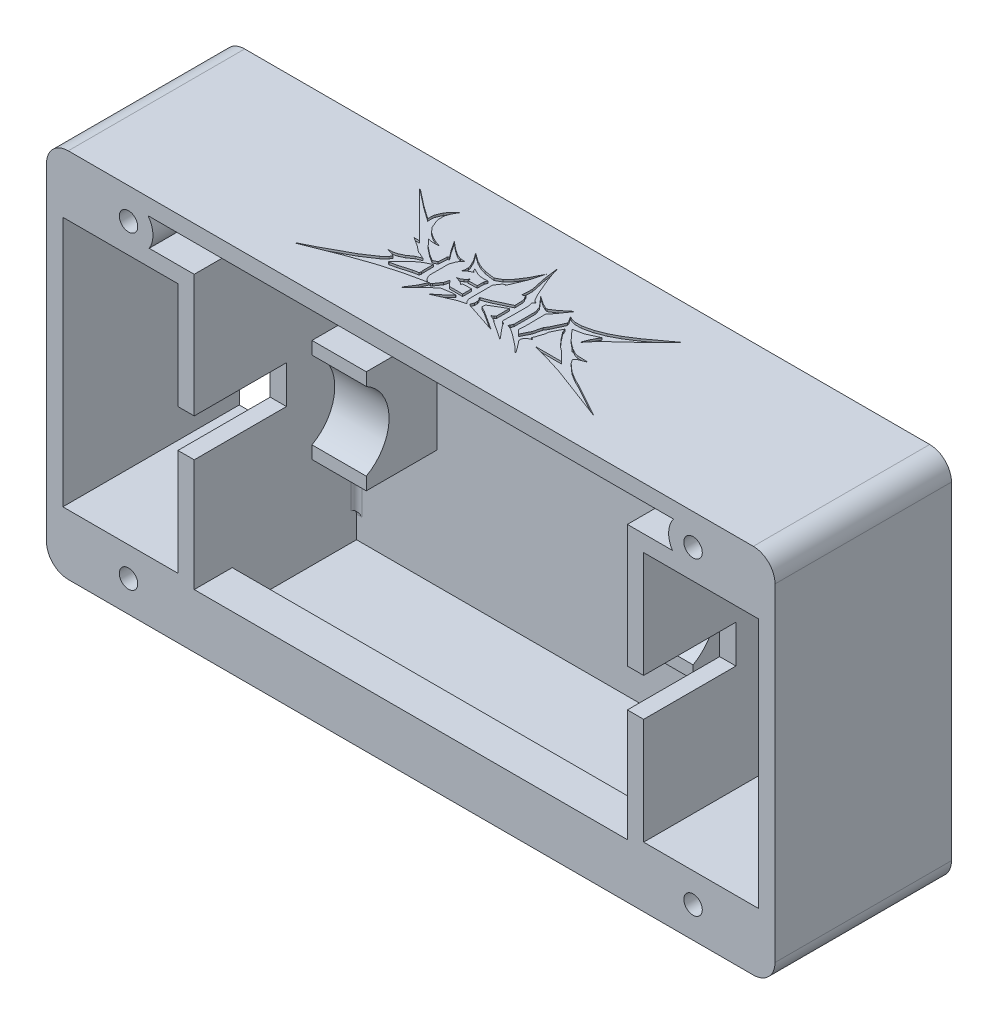
SolidWorks part; units mm, degrees
material "Overture Super PLA Plus"
ref_plane "Front Plane" through (0, 0, 0) normal (0, 0, 1) x (1, 0, 0)
ref_plane "Top Plane" through (0, 0, 0) normal (0, 1, 0) x (1, 0, 0)
ref_plane "Right Plane" through (0, 0, 0) normal (1, 0, 0) x (0, 0, -1)
sketch "Base_Footprint" plane through (0, 0, 0) normal (0, 0, 1) x (1, 0, 0)
  line L1 (-67.1, -34.2) -> (67.1, -34.2)
  line L2 (-67.1, -34.2) -> (-67.1, 34.2)
  line L3 (-67.1, 34.2) -> (67.1, 34.2)
  line L4 (67.1, -34.2) -> (67.1, 34.2)
  dimension "R1_Width" = 134.2
  dimension "R1_Length" = 68.4
  dimension "R1_X" = 67.1
  dimension "R1_Y" = 34.2
extrude "Unbroken_Floor" add sketch "Base_Footprint" along normal blind 2.6
sketch "Shell_Profile" plane through (0, 0, 0) normal (0, 0, 1) x (1, 0, 0)
  line L1 (-67.1, -34.2) -> (67.1, -34.2)
  line L2 (-67.1, -34.2) -> (-67.1, 34.2)
  line L3 (-67.1, 34.2) -> (67.1, 34.2)
  line L4 (67.1, -34.2) -> (67.1, 34.2)
  line L6 (-64.1, -31.2) -> (64.1, -31.2)
  line L7 (-64.1, -31.2) -> (-64.1, 31.2)
  line L8 (-64.1, 31.2) -> (64.1, 31.2)
  line L9 (64.1, -31.2) -> (64.1, 31.2)
  dimension "R1_Width" = 134.2
  dimension "R1_Length" = 68.4
  dimension "R1_X" = 67.1
  dimension "R1_Y" = 34.2
  dimension "R2_Width" = 128.2
  dimension "R2_Length" = 62.4
  dimension "R2_X" = 64.1
  dimension "R2_Y" = 31.2
extrude "Three_mm_Perimeter" add sketch "Shell_Profile" along normal blind 32.5
sketch "Wheel_Well_Profile" plane through (0, 0, 0) normal (0, 0, 1) x (1, 0, 0)
  line L1 (42.9, -23.1) -> (64.1, -23.1)
  line L2 (42.9, -23.1) -> (42.9, 23.1)
  line L3 (42.9, 23.1) -> (64.1, 23.1)
  line L4 (64.1, -23.1) -> (64.1, 23.1)
  line L6 (-64.1, -23.1) -> (-42.9, -23.1)
  line L7 (-64.1, -23.1) -> (-64.1, 23.1)
  line L8 (-64.1, 23.1) -> (-42.9, 23.1)
  line L9 (-42.9, -23.1) -> (-42.9, 23.1)
  dimension "R2_X" = 64.1
  dimension "R1_Width" = 21.2
  dimension "R1_Length" = 46.2
  dimension "R1_X" = 42.9
  dimension "R1_Y" = 23.1
  dimension "R2_Width" = 21.2
  dimension "R2_Length" = 46.2
  dimension "R2_Y" = 23.1
extrude "Open_Wheel_Wells" cut sketch "Wheel_Well_Profile" against normal blind 38 from offset 36
sketch "Wheel_Guard_Profile" plane through (0, 0, 0) normal (0, 0, 1) x (1, 0, 0)
  line L1 (39.9, -23.1) -> (42.9, -23.1)
  line L2 (39.9, -23.1) -> (39.9, 23.1)
  line L3 (39.9, 23.1) -> (42.9, 23.1)
  line L4 (42.9, -23.1) -> (42.9, 23.1)
  line L6 (-42.9, -23.1) -> (-39.9, -23.1)
  line L7 (-42.9, -23.1) -> (-42.9, 23.1)
  line L8 (-42.9, 23.1) -> (-39.9, 23.1)
  line L9 (-39.9, -23.1) -> (-39.9, 23.1)
  dimension "R1_Width" = 3
  dimension "R1_Length" = 46.2
  dimension "R1_X" = 39.9
  dimension "R1_Y" = 23.1
  dimension "R2_Width" = 3
  dimension "R2_Length" = 46.2
  dimension "R2_X" = 42.9
  dimension "R2_Y" = 23.1
extrude "Inner_Wheel_Guards" add sketch "Wheel_Guard_Profile" along normal blind 32.5
sketch "Wheel_Return_Profile" plane through (0, 0, 0) normal (0, 0, 1) x (1, 0, 0)
  line L1 (-64.1, -26.1) -> (-39.9, -26.1)
  line L2 (-64.1, -26.1) -> (-64.1, -23.1)
  line L3 (-64.1, -23.1) -> (-39.9, -23.1)
  line L4 (-39.9, -26.1) -> (-39.9, -23.1)
  line L6 (-64.1, 23.1) -> (-39.9, 23.1)
  line L7 (-64.1, 23.1) -> (-64.1, 26.1)
  line L8 (-64.1, 26.1) -> (-39.9, 26.1)
  line L9 (-39.9, 23.1) -> (-39.9, 26.1)
  line L11 (39.9, -26.1) -> (64.1, -26.1)
  line L12 (39.9, -26.1) -> (39.9, -23.1)
  line L13 (39.9, -23.1) -> (64.1, -23.1)
  line L14 (64.1, -26.1) -> (64.1, -23.1)
  line L16 (39.9, 23.1) -> (64.1, 23.1)
  line L17 (39.9, 23.1) -> (39.9, 26.1)
  line L18 (39.9, 26.1) -> (64.1, 26.1)
  line L19 (64.1, 23.1) -> (64.1, 26.1)
  dimension "R1_Width" = 24.2
  dimension "R1_Length" = 3
  dimension "R1_X" = 64.1
  dimension "R1_Y" = 26.1
  dimension "R2_Width" = 24.2
  dimension "R2_Length" = 3
  dimension "R2_X" = 64.1
  dimension "R2_Y" = 23.1
  dimension "R3_Width" = 24.2
  dimension "R3_Length" = 3
  dimension "R3_X" = 39.9
  dimension "R3_Y" = 26.1
  dimension "R4_Width" = 24.2
  dimension "R4_Length" = 3
  dimension "R4_X" = 39.9
  dimension "R4_Y" = 23.1
extrude "Wheel_Return_Ribs" add sketch "Wheel_Return_Profile" along normal blind 32.5
sketch "Shaft_Drop_In_Profile" plane through (0, 0, 0) normal (0, 0, 1) x (1, 0, 0)
  line L1 (-43.2, -3.5) -> (-39.5, -3.5)
  line L2 (-43.2, -3.5) -> (-43.2, 3.5)
  line L3 (-43.2, 3.5) -> (-39.5, 3.5)
  line L4 (-39.5, -3.5) -> (-39.5, 3.5)
  line L6 (39.5, -3.5) -> (43.2, -3.5)
  line L7 (39.5, -3.5) -> (39.5, 3.5)
  line L8 (39.5, 3.5) -> (43.2, 3.5)
  line L9 (43.2, -3.5) -> (43.2, 3.5)
  dimension "R1_Width" = 3.7
  dimension "R1_Length" = 7
  dimension "R1_X" = 43.2
  dimension "R1_Y" = 3.5
  dimension "R2_Width" = 3.7
  dimension "R2_Length" = 7
  dimension "R2_X" = 39.5
  dimension "R2_Y" = 3.5
extrude "Open_Shaft_Notches" cut sketch "Shaft_Drop_In_Profile" against normal blind 17 from offset 32.5
sketch "Lower_Cradle_Blocks_Profile" plane through (0, 0, 0) normal (0, 0, 1) x (1, 0, 0)
  line L1 (-35.1, -9.5) -> (-25.1, -9.5)
  line L2 (-35.1, -9.5) -> (-35.1, 9.5)
  line L3 (-35.1, 9.5) -> (-25.1, 9.5)
  line L4 (-25.1, -9.5) -> (-25.1, 9.5)
  line L6 (25.1, -9.5) -> (35.1, -9.5)
  line L7 (25.1, -9.5) -> (25.1, 9.5)
  line L8 (25.1, 9.5) -> (35.1, 9.5)
  line L9 (35.1, -9.5) -> (35.1, 9.5)
  dimension "R1_Width" = 10
  dimension "R1_Length" = 19
  dimension "R1_X" = 35.1
  dimension "R1_Y" = 9.5
  dimension "R2_Width" = 10
  dimension "R2_Length" = 19
  dimension "R2_X" = 25.1
  dimension "R2_Y" = 9.5
extrude "Lower_Motor_Cradles" add sketch "Lower_Cradle_Blocks_Profile" along normal blind 15.6
sketch "Lower_Cradle_Radius_Profile" plane through (0, 0, 0) normal (1, 0, 0) x (0, 0, -1)
  circle A0 centre (-19.6, 0) radius 8.2
  dimension "C1_Diameter" = 16.4
  dimension "Motor_Axis_Height" = 19.6
extrude "Lower_Cradle_Seats_R8p2" cut sketch "Lower_Cradle_Radius_Profile" against normal blind 72 from offset 36
sketch "Battery_Side_Guides_Profile" plane through (0, 0, 0) normal (0, 0, 1) x (1, 0, 0)
  line L1 (-31.5, 10) -> (-28.5, 10)
  line L2 (-31.5, 10) -> (-31.5, 31.2)
  line L3 (-31.5, 31.2) -> (-28.5, 31.2)
  line L4 (-28.5, 10) -> (-28.5, 31.2)
  line L6 (28.5, 10) -> (31.5, 10)
  line L7 (28.5, 10) -> (28.5, 31.2)
  line L8 (28.5, 31.2) -> (31.5, 31.2)
  line L9 (31.5, 10) -> (31.5, 31.2)
  dimension "R1_Width" = 3
  dimension "R1_Length" = 21.2
  dimension "R1_X" = 31.5
  dimension "R1_Y" = 10
  dimension "R2_Width" = 3
  dimension "R2_Length" = 21.2
  dimension "R2_X" = 28.5
  dimension "R2_Y" = 10
extrude "Battery_Side_Guides" add sketch "Battery_Side_Guides_Profile" along normal blind 5.6
sketch "Lid_Screw_Boss_Profile" plane through (0, 0, 0) normal (0, 0, 1) x (1, 0, 0)
  circle A0 centre (-52, -28.5) radius 4.5
  circle A1 centre (-52, 28.5) radius 4.5
  circle A2 centre (52, -28.5) radius 4.5
  circle A3 centre (52, 28.5) radius 4.5
  dimension "C1_Diameter" = 9
  dimension "C2_Diameter" = 9
  dimension "C3_Diameter" = 9
  dimension "C4_Diameter" = 9
extrude "Reinforced_M3_Bosses" add sketch "Lid_Screw_Boss_Profile" along normal blind 32.5
sketch "M3_Through_Holes_Profile" plane through (0, 0, 0) normal (0, 0, 1) x (1, 0, 0)
  circle A0 centre (-52, -28.5) radius 1.7
  circle A1 centre (-52, 28.5) radius 1.7
  circle A2 centre (52, -28.5) radius 1.7
  circle A3 centre (52, 28.5) radius 1.7
  dimension "C1_Diameter" = 3.4
  dimension "C2_Diameter" = 3.4
  dimension "C3_Diameter" = 3.4
  dimension "C4_Diameter" = 3.4
extrude "M3_Through_Holes" cut sketch "M3_Through_Holes_Profile" against normal blind 36 from offset 35.5
sketch "Captive_Nut_Pockets_Profile" plane through (0, 0, 0) normal (0, 0, 1) x (1, 0, 0)
  line L0 (-48.7091, -28.5) -> (-50.3546, -25.65)
  line L1 (-50.3546, -25.65) -> (-53.6454, -25.65)
  line L2 (-53.6454, -25.65) -> (-55.2909, -28.5)
  line L3 (-55.2909, -28.5) -> (-53.6454, -31.35)
  line L4 (-53.6454, -31.35) -> (-50.3546, -31.35)
  line L5 (-50.3546, -31.35) -> (-48.7091, -28.5)
  line L6 (-48.7091, 28.5) -> (-50.3546, 31.35)
  line L7 (-50.3546, 31.35) -> (-53.6454, 31.35)
  line L8 (-53.6454, 31.35) -> (-55.2909, 28.5)
  line L9 (-55.2909, 28.5) -> (-53.6454, 25.65)
  line L10 (-53.6454, 25.65) -> (-50.3546, 25.65)
  line L11 (-50.3546, 25.65) -> (-48.7091, 28.5)
  line L12 (55.2909, -28.5) -> (53.6454, -25.65)
  line L13 (53.6454, -25.65) -> (50.3546, -25.65)
  line L14 (50.3546, -25.65) -> (48.7091, -28.5)
  line L15 (48.7091, -28.5) -> (50.3546, -31.35)
  line L16 (50.3546, -31.35) -> (53.6454, -31.35)
  line L17 (53.6454, -31.35) -> (55.2909, -28.5)
  line L18 (55.2909, 28.5) -> (53.6454, 31.35)
  line L19 (53.6454, 31.35) -> (50.3546, 31.35)
  line L20 (50.3546, 31.35) -> (48.7091, 28.5)
  line L21 (48.7091, 28.5) -> (50.3546, 25.65)
  line L22 (50.3546, 25.65) -> (53.6454, 25.65)
  line L23 (53.6454, 25.65) -> (55.2909, 28.5)
extrude "M3_Hex_Nut_Pockets_Underside" cut sketch "Captive_Nut_Pockets_Profile" against normal blind 2.7 from offset 2.6
fillet "Outer_Corners_R4" radius 4 4 edges at (-67.1, 34.2, 16.25) (67.1, 34.2, 16.25) (67.1, -34.2, 16.25) (-67.1, -34.2, 16.25)
fillet "Inner_Corners_R1" radius 1 4 edges at (-64.1, -31.2, 17.55) (64.1, -31.2, 17.55) (64.1, 31.2, 17.55) (-64.1, 31.2, 17.55)
fillet "Wheel_Return_Root_Fillets_R1" radius 1 10 edges at (-44.0467, -26.1, 2.6) (-59.9533, -26.1, 2.6) (44.0467, 26.1, 2.6) (59.9533, 26.1, 2.6) (44.0467, -26.1, 2.6) (59.9533, -26.1, 2.6) (-44.0467, 26.1, 2.6) (-59.9533, 26.1, 2.6) (-39.9, 0, 2.6) (39.9, 0, 2.6)
sketch "VIPER_Wordmark_Native_Profile" plane through (0, 0, 0) normal (0, 1, 0) x (1, 0, 0)
  line L0 (27.5, -26.3235) -> (17.4068, -22.5385)
  line L1 (17.4068, -22.5385) -> (13.8978, -21.4346)
  line L2 (13.8978, -21.4346) -> (11.3351, -20.7643)
  line L3 (11.3351, -20.7643) -> (11.2957, -20.6855)
  line L4 (11.2957, -20.6855) -> (15.948, -20.6855)
  line L5 (15.948, -20.6855) -> (14.2133, -18.9507)
  line L6 (14.2133, -18.9507) -> (13.543, -18.4776)
  line L7 (13.543, -18.4776) -> (12.3208, -17.1371)
  line L8 (12.3208, -17.1371) -> (11.3746, -15.8754)
  line L9 (11.3746, -15.8754) -> (11.0986, -15.1658)
  line L10 (11.0986, -15.1658) -> (10.0735, -17.2159)
  line L11 (10.0735, -17.2159) -> (10.0735, -17.6496)
  line L12 (10.0735, -17.6496) -> (9.5609, -19.2267)
  line L13 (9.5609, -19.2267) -> (9.3638, -19.5815)
  line L14 (9.3638, -19.5815) -> (9.7975, -19.8181)
  line L15 (9.7975, -19.8181) -> (9.7975, -19.897)
  line L16 (9.7975, -19.897) -> (9.5215, -19.9364)
  line L17 (9.5215, -19.9364) -> (9.0878, -20.2124)
  line L18 (9.0878, -20.2124) -> (8.7724, -20.5278)
  line L19 (8.7724, -20.5278) -> (8.6147, -20.8432)
  line L20 (8.6147, -20.8432) -> (8.6541, -21.2375)
  line L21 (8.6541, -21.2375) -> (9.7581, -22.6568)
  line L22 (9.7581, -22.6568) -> (10.31, -23.4453)
  line L23 (10.31, -23.4453) -> (10.2706, -23.5242)
  line L24 (10.2706, -23.5242) -> (9.1272, -22.4597)
  line L25 (9.1272, -22.4597) -> (7.1559, -20.922)
  line L26 (7.1559, -20.922) -> (5.9731, -20.1335)
  line L27 (5.9731, -20.1335) -> (5.224, -19.8575)
  line L28 (5.224, -19.8575) -> (5.4211, -19.621)
  line L29 (5.4211, -19.621) -> (5.6183, -19.069)
  line L30 (5.6183, -19.069) -> (5.6183, -15.2446)
  line L31 (5.6183, -15.2446) -> (5.5394, -14.8504)
  line L32 (5.5394, -14.8504) -> (5.224, -14.0224)
  line L33 (5.224, -14.0224) -> (3.6864, -12.2482)
  line L34 (3.6864, -12.2482) -> (5.0269, -13.155)
  line L35 (5.0269, -13.155) -> (5.9731, -13.6281)
  line L36 (5.9731, -13.6281) -> (6.2491, -13.6676)
  line L37 (6.2491, -13.6676) -> (7.4713, -12.879)
  line L38 (7.4713, -12.879) -> (9.3244, -11.3414)
  line L39 (9.3244, -11.3414) -> (7.6685, -13.707)
  line L40 (7.6685, -13.707) -> (6.9194, -14.5744)
  line L41 (6.9194, -14.5744) -> (6.9588, -18.1228)
  line L42 (6.9588, -18.1228) -> (6.8799, -19.5815)
  line L43 (6.8799, -19.5815) -> (7.629, -20.2518)
  line L44 (7.629, -20.2518) -> (8.457, -18.5959)
  line L45 (8.457, -18.5959) -> (8.8513, -17.0188)
  line L46 (8.8513, -17.0188) -> (9.2849, -16.3091)
  line L47 (9.2849, -16.3091) -> (10.3495, -14.0224)
  line L48 (10.3495, -14.0224) -> (10.1918, -13.5887)
  line L49 (10.1918, -13.5887) -> (9.6398, -12.7213)
  line L50 (9.6398, -12.7213) -> (10.2312, -12.9973)
  line L51 (10.2312, -12.9973) -> (10.9014, -13.155)
  line L52 (10.9014, -13.155) -> (12.1237, -13.155)
  line L53 (12.1237, -13.155) -> (13.9767, -12.7213)
  line L54 (13.9767, -12.7213) -> (15.7115, -12.0511)
  line L55 (15.7115, -12.0511) -> (17.3674, -11.1837)
  line L56 (17.3674, -11.1837) -> (19.5358, -9.8038)
  line L57 (19.5358, -9.8038) -> (24.267, -6.3342)
  line L58 (24.267, -6.3342) -> (20.0484, -10.474)
  line L59 (20.0484, -10.474) -> (17.4068, -12.9185)
  line L60 (17.4068, -12.9185) -> (15.5932, -14.7321)
  line L61 (15.5932, -14.7321) -> (14.6864, -15.836)
  line L62 (14.6864, -15.836) -> (14.647, -15.7177)
  line L63 (14.647, -15.7177) -> (15.0806, -14.6138)
  line L64 (15.0806, -14.6138) -> (15.8692, -13.155)
  line L65 (15.8692, -13.155) -> (13.6219, -14.1801)
  line L66 (13.6219, -14.1801) -> (11.7688, -14.5744)
  line L67 (11.7688, -14.5744) -> (13.5036, -16.4668)
  line L68 (13.5036, -16.4668) -> (14.4104, -17.2159)
  line L69 (14.4104, -17.2159) -> (14.7258, -17.3737)
  line L70 (14.7258, -17.3737) -> (15.0018, -17.7679)
  line L71 (15.0018, -17.7679) -> (15.1201, -17.6891)
  line L72 (15.1201, -17.6891) -> (15.9086, -18.1228)
  line L73 (15.9086, -18.1228) -> (16.5, -18.2805)
  line L74 (16.5, -18.2805) -> (18.4713, -18.3593)
  line L75 (18.4713, -18.3593) -> (17.2097, -18.8719)
  line L76 (17.2097, -18.8719) -> (16.8154, -19.1478)
  line L77 (16.8154, -19.1478) -> (16.6577, -19.3844)
  line L78 (16.6577, -19.3844) -> (17.1308, -20.0941)
  line L79 (17.1308, -20.0941) -> (18.5502, -21.3557)
  line L80 (18.5502, -21.3557) -> (20.0878, -22.302)
  line L81 (20.0878, -22.302) -> (21.31, -22.8934)
  line L82 (21.31, -22.8934) -> (27.5, -26.3235)
  line L83 (-27.4211, -26.2841) -> (-27.5, -26.2841)
  line L84 (-27.5, -26.2841) -> (-27.4606, -26.2052)
  line L85 (-27.4606, -26.2052) -> (-25.0161, -24.983)
  line L86 (-25.0161, -24.983) -> (-19.9695, -22.2231)
  line L87 (-19.9695, -22.2231) -> (-17.6039, -20.6461)
  line L88 (-17.6039, -20.6461) -> (-16.6971, -19.7787)
  line L89 (-16.6971, -19.7787) -> (-16.4211, -19.345)
  line L90 (-16.4211, -19.345) -> (-16.8943, -19.1084)
  line L91 (-16.8943, -19.1084) -> (-18.0771, -18.793)
  line L92 (-18.0771, -18.793) -> (-17.1308, -18.7536)
  line L93 (-17.1308, -18.7536) -> (-16.3029, -18.5565)
  line L94 (-16.3029, -18.5565) -> (-15.3961, -18.1228)
  line L95 (-15.3961, -18.1228) -> (-14.2527, -17.3342)
  line L96 (-14.2527, -17.3342) -> (-13.3065, -16.9794)
  line L97 (-13.3065, -16.9794) -> (-14.3315, -16.5063)
  line L98 (-14.3315, -16.5063) -> (-14.6075, -16.4668)
  line L99 (-14.6075, -16.4668) -> (-15.7903, -15.5206)
  line L100 (-15.7903, -15.5206) -> (-17.4068, -14.4955)
  line L101 (-17.4068, -14.4955) -> (-16.4211, -14.4955)
  line L102 (-16.4211, -14.4955) -> (-24.6219, -6.2554)
  line L103 (-24.6219, -6.2554) -> (-24.6219, -6.1765)
  line L104 (-24.6219, -6.1765) -> (-24.4642, -6.2554)
  line L105 (-24.4642, -6.2554) -> (-21.5466, -8.5421)
  line L106 (-21.5466, -8.5421) -> (-19.1416, -10.2375)
  line L107 (-19.1416, -10.2375) -> (-19.181, -9.4095)
  line L108 (-19.181, -9.4095) -> (-19.1022, -8.9758)
  line L109 (-19.1022, -8.9758) -> (-18.629, -7.8719)
  line L110 (-18.629, -7.8719) -> (-18.1165, -7.1622)
  line L111 (-18.1165, -7.1622) -> (-17.0914, -6.1765)
  line L112 (-17.0914, -6.1765) -> (-17.7616, -7.3593)
  line L113 (-17.7616, -7.3593) -> (-18.0376, -8.1873)
  line L114 (-18.0376, -8.1873) -> (-18.0771, -9.2518)
  line L115 (-18.0771, -9.2518) -> (-17.9588, -9.8038)
  line L116 (-17.9588, -9.8038) -> (-17.3674, -11.2231)
  line L117 (-17.3674, -11.2231) -> (-16.6183, -12.0511)
  line L118 (-16.6183, -12.0511) -> (-15.7115, -12.6819)
  line L119 (-15.7115, -12.6819) -> (-14.8441, -13.1156)
  line L120 (-14.8441, -13.1156) -> (-13.7007, -13.5099)
  line L121 (-13.7007, -13.5099) -> (-14.9229, -13.5493)
  line L122 (-14.9229, -13.5493) -> (-15.8297, -13.3916)
  line L123 (-15.8297, -13.3916) -> (-14.6864, -14.6138)
  line L124 (-14.6864, -14.6138) -> (-13.3065, -15.7177)
  line L125 (-13.3065, -15.7177) -> (-12.0842, -16.4668)
  line L126 (-12.0842, -16.4668) -> (-11.3351, -16.112)
  line L127 (-11.3351, -16.112) -> (-11.2563, -14.6138)
  line L128 (-11.2563, -14.6138) -> (-11.2168, -14.4561)
  line L129 (-11.2168, -14.4561) -> (-10.9409, -14.4167)
  line L130 (-10.9409, -14.4167) -> (-11.8082, -13.3127)
  line L131 (-11.8082, -13.3127) -> (-13.1093, -11.3808)
  line L132 (-13.1093, -11.3808) -> (-11.7688, -12.4848)
  line L133 (-11.7688, -12.4848) -> (-10.6649, -13.2339)
  line L134 (-10.6649, -13.2339) -> (-9.7975, -13.5887)
  line L135 (-9.7975, -13.5887) -> (-8.8513, -13.6281)
  line L136 (-8.8513, -13.6281) -> (-9.3638, -14.1013)
  line L137 (-9.3638, -14.1013) -> (-9.6398, -14.4955)
  line L138 (-9.6398, -14.4955) -> (-9.9946, -15.5206)
  line L139 (-9.9946, -15.5206) -> (-9.9946, -19.1478)
  line L140 (-9.9946, -19.1478) -> (-9.6398, -19.897)
  line L141 (-9.6398, -19.897) -> (-9.0484, -20.3306)
  line L142 (-9.0484, -20.3306) -> (-12.8728, -21.1586)
  line L143 (-12.8728, -21.1586) -> (-16.8548, -22.302)
  line L144 (-16.8548, -22.302) -> (-21.2312, -23.8396)
  line L145 (-21.2312, -23.8396) -> (-27.4211, -26.2841)
  line L146 (-10.586, -23.5636) -> (-10.6254, -23.4848)
  line L147 (-10.6254, -23.4848) -> (-9.4427, -21.6317)
  line L148 (-9.4427, -21.6317) -> (-8.8513, -20.2912)
  line L149 (-8.8513, -20.2912) -> (-8.5753, -20.2912)
  line L150 (-8.5753, -20.2912) -> (-8.3781, -20.1335)
  line L151 (-8.3781, -20.1335) -> (-7.5502, -18.9113)
  line L152 (-7.5502, -18.9113) -> (-7.2742, -18.0045)
  line L153 (-7.2742, -18.0045) -> (-6.3674, -19.0296)
  line L154 (-6.3674, -19.0296) -> (-3.9229, -19.0296)
  line L155 (-3.9229, -19.0296) -> (-3.9229, -17.3737)
  line L156 (-3.9229, -17.3737) -> (-5.5789, -17.4131)
  line L157 (-5.5789, -17.4131) -> (-5.6183, -17.7679)
  line L158 (-5.6183, -17.7679) -> (-5.776, -17.5314)
  line L159 (-5.776, -17.5314) -> (-6.1308, -17.2948)
  line L160 (-6.1308, -17.2948) -> (-7.1559, -16.9794)
  line L161 (-7.1559, -16.9794) -> (-6.6039, -16.8217)
  line L162 (-6.6039, -16.8217) -> (-6.1308, -16.5457)
  line L163 (-6.1308, -16.5457) -> (-5.6183, -15.9937)
  line L164 (-5.6183, -15.9937) -> (-5.5394, -16.388)
  line L165 (-5.5394, -16.388) -> (-3.9229, -16.3486)
  line L166 (-3.9229, -16.3486) -> (-3.8835, -15.0869)
  line L167 (-3.8835, -15.0869) -> (-3.6864, -14.6138)
  line L168 (-3.6864, -14.6138) -> (-4.6326, -14.6532)
  line L169 (-4.6326, -14.6532) -> (-5.5, -14.5349)
  line L170 (-5.5, -14.5349) -> (-6.8011, -13.9041)
  line L171 (-6.8011, -13.9041) -> (-6.6039, -14.3772)
  line L172 (-6.6039, -14.3772) -> (-6.3674, -14.4561)
  line L173 (-6.3674, -14.4561) -> (-6.3674, -14.5349)
  line L174 (-6.3674, -14.5349) -> (-6.9588, -14.8109)
  line L175 (-6.9588, -14.8109) -> (-7.7079, -15.4023)
  line L176 (-7.7079, -15.4023) -> (-7.5896, -14.9686)
  line L177 (-7.5896, -14.9686) -> (-7.5896, -14.2984)
  line L178 (-7.5896, -14.2984) -> (-7.7867, -13.6281)
  line L179 (-7.7867, -13.6281) -> (-8.3387, -12.5636)
  line L180 (-8.3387, -12.5636) -> (-9.2455, -11.302)
  line L181 (-9.2455, -11.302) -> (-7.7079, -12.4059)
  line L182 (-7.7079, -12.4059) -> (-6.6828, -12.9185)
  line L183 (-6.6828, -12.9185) -> (-5.4606, -13.3127)
  line L184 (-5.4606, -13.3127) -> (-3.6075, -13.5887)
  line L185 (-3.6075, -13.5887) -> (-2.543, -12.9973)
  line L186 (-2.543, -12.9973) -> (-1.5573, -11.9722)
  line L187 (-1.5573, -11.9722) -> (-0.414, -10.2375)
  line L188 (-0.414, -10.2375) -> (0.6505, -8.069)
  line L189 (0.6505, -8.069) -> (-0.0986, -10.7106)
  line L190 (-0.0986, -10.7106) -> (-1.3602, -13.707)
  line L191 (-1.3602, -13.707) -> (-1.5179, -13.5887)
  line L192 (-1.5179, -13.5887) -> (-1.7545, -13.707)
  line L193 (-1.7545, -13.707) -> (-2.1093, -14.1013)
  line L194 (-2.1093, -14.1013) -> (-2.5824, -14.8898)
  line L195 (-2.5824, -14.8898) -> (-2.5824, -19.2267)
  line L196 (-2.5824, -19.2267) -> (-2.3459, -19.7787)
  line L197 (-2.3459, -19.7787) -> (-1.9516, -20.1729)
  line L198 (-1.9516, -20.1729) -> (-3.4104, -20.5672)
  line L199 (-3.4104, -20.5672) -> (-7.1953, -22.2231)
  line L200 (-7.1953, -22.2231) -> (-5.9731, -21.2769)
  line L201 (-5.9731, -21.2769) -> (-4.3961, -19.8575)
  line L202 (-4.3961, -19.8575) -> (-4.3961, -19.7787)
  line L203 (-4.3961, -19.7787) -> (-5.1452, -19.8181)
  line L204 (-5.1452, -19.8181) -> (-6.8799, -20.0941)
  line L205 (-6.8799, -20.0941) -> (-8.733, -21.6711)
  line L206 (-8.733, -21.6711) -> (-10.586, -23.5636)
  line L207 (6.8405, -22.8934) -> (3.2527, -20.4884)
  line L208 (3.2527, -20.4884) -> (3.1344, -20.3306)
  line L209 (3.1344, -20.3306) -> (2.0699, -19.8575)
  line L210 (2.0699, -19.8575) -> (2.5036, -19.6604)
  line L211 (2.5036, -19.6604) -> (2.7007, -19.4238)
  line L212 (2.7007, -19.4238) -> (2.7007, -17.0188)
  line L213 (2.7007, -17.0188) -> (-0.0591, -18.6747)
  line L214 (-0.0591, -18.6747) -> (-0.0986, -19.3056)
  line L215 (-0.0986, -19.3056) -> (0.8871, -19.8181)
  line L216 (0.8871, -19.8181) -> (4.3566, -22.0654)
  line L217 (4.3566, -22.0654) -> (-1.3996, -20.1729)
  line L218 (-1.3996, -20.1729) -> (-1.6362, -20.0152)
  line L219 (-1.6362, -20.0152) -> (-1.3996, -19.345)
  line L220 (-1.3996, -19.345) -> (-1.3996, -18.793)
  line L221 (-1.3996, -18.793) -> (-1.5573, -18.3593)
  line L222 (-1.5573, -18.3593) -> (-1.7939, -18.0833)
  line L223 (-1.7939, -18.0833) -> (-1.7545, -18.0045)
  line L224 (-1.7545, -18.0045) -> (-0.2957, -17.4525)
  line L225 (-0.2957, -17.4525) -> (2.7007, -16.0332)
  line L226 (2.7007, -16.0332) -> (2.6613, -14.6532)
  line L227 (2.6613, -14.6532) -> (2.5036, -14.0618)
  line L228 (2.5036, -14.0618) -> (2.2276, -13.707)
  line L229 (2.2276, -13.707) -> (2.1882, -13.431)
  line L230 (2.1882, -13.431) -> (1.6756, -13.7464)
  line L231 (1.6756, -13.7464) -> (1.7545, -11.8539)
  line L232 (1.7545, -11.8539) -> (1.1237, -8.897)
  line L233 (1.1237, -8.897) -> (0.8082, -6.4131)
  line L234 (0.8082, -6.4131) -> (0.8871, -6.4525)
  line L235 (0.8871, -6.4525) -> (1.0448, -7.1622)
  line L236 (1.0448, -7.1622) -> (1.7151, -9.0152)
  line L237 (1.7151, -9.0152) -> (3.0556, -12.1299)
  line L238 (3.0556, -12.1299) -> (3.6864, -13.3127)
  line L239 (3.6864, -13.3127) -> (4.0806, -13.6281)
  line L240 (4.0806, -13.6281) -> (4.2778, -13.6676)
  line L241 (4.2778, -13.6676) -> (3.8835, -14.1013)
  line L242 (3.8835, -14.1013) -> (4.0806, -15.0081)
  line L243 (4.0806, -15.0081) -> (4.0412, -19.621)
  line L244 (4.0412, -19.621) -> (4.2384, -19.8181)
  line L245 (4.2384, -19.8181) -> (4.4749, -19.897)
  line L246 (4.4749, -19.897) -> (5.0269, -20.7249)
  line L247 (5.0269, -20.7249) -> (6.8405, -22.8934)
  line L248 (-15.9086, -20.6855) -> (-15.7903, -20.7249)
  line L249 (-15.7903, -20.7249) -> (-14.5681, -20.4489)
  line L250 (-14.5681, -20.4489) -> (-12.3996, -19.8181)
  line L251 (-12.3996, -19.8181) -> (-11.3746, -19.621)
  line L252 (-11.3746, -19.621) -> (-11.2563, -19.3056)
  line L253 (-11.2563, -19.3056) -> (-11.3351, -18.9113)
  line L254 (-11.3351, -18.9113) -> (-11.3351, -17.0188)
  line L255 (-11.3351, -17.0188) -> (-12.6362, -17.6496)
  line L256 (-12.6362, -17.6496) -> (-13.819, -18.517)
  line L257 (-13.819, -18.517) -> (-15.9086, -20.6855)
extrude "VIPER_Rear_Engraved" cut sketch "VIPER_Wordmark_Native_Profile" against normal blind 0.4 from offset 34.2
sketch "Sketch1" plane through (0, 0, 0) normal (0, 0, 1) x (1, 0, 0)
  line L0 (0, 0) -> (0, -36.802) construction
  line L1 (-48.4, -31.2) -> (-39.9, -31.2)
  line L2 (-48.4, -31.2) -> (-48.4, -26.1)
  line L3 (-48.4, -26.1) -> (-39.9, -26.1)
  line L4 (-39.9, -31.2) -> (-39.9, -26.1)
  line L5 (48.4, -31.2) -> (48.4, -26.1)
  line L6 (48.4, -26.1) -> (39.9, -26.1)
  line L7 (39.9, -31.2) -> (39.9, -26.1)
  line L8 (48.4, -31.2) -> (39.9, -31.2)
extrude "Boss-Extrude1" add sketch "Sketch1" along normal blind 32.5
sketch "Sketch2" plane through (-39.9, 0, 0) normal (1, 0, 0) x (0, 0, -1)
  line L1 (-32.5, -31.2) -> (-25.5, -31.2)
  line L2 (-32.5, -31.2) -> (-32.5, -24.2)
  line L3 (-32.5, -24.2) -> (-25.5, -24.2)
  line L4 (-25.5, -31.2) -> (-25.5, -24.2)
  dimension "D1" = 7
  dimension "D2" = 7
extrude "Boss-Extrude2" add sketch "Sketch2" along normal blind 82.5 and the other way blind 2
sketch "Sketch3" plane through (0, 0, 0) normal (0, 0, 1) x (1, 0, 0)
  line L1 (-55.6, 31.2) -> (-64.1, 31.2)
  line L2 (-55.6, 31.2) -> (-55.6, 26.1)
  line L3 (-55.6, 26.1) -> (-64.1, 26.1)
  line L4 (-64.1, 31.2) -> (-64.1, 26.1)
  line L5 (-55.6, -31.2) -> (-64.1, -31.2)
  line L6 (-55.6, -31.2) -> (-55.6, -26.1)
  line L7 (-55.6, -26.1) -> (-64.1, -26.1)
  line L8 (-64.1, -31.2) -> (-64.1, -26.1)
  line L9 (55.6, -31.2) -> (64.1, -31.2)
  line L10 (55.6, -31.2) -> (55.6, -26.1)
  line L11 (55.6, -26.1) -> (64.1, -26.1)
  line L12 (64.1, -31.2) -> (64.1, -26.1)
  line L13 (55.6, 31.2) -> (64.1, 31.2)
  line L14 (55.6, 31.2) -> (55.6, 26.1)
  line L15 (55.6, 26.1) -> (64.1, 26.1)
  line L16 (64.1, 31.2) -> (64.1, 26.1)
extrude "Boss-Extrude5" add sketch "Sketch3" along normal blind 32.5
sketch "Sketch6" plane through (0, -34.2, 0) normal (0, -1, 0) x (1, 0, 0)
  line L0 (0, 0) -> (0, 32.5) construction
  line L1 (-63.1, 32.5) -> (63.1, 32.5) construction
  line L2 (-63.1, 0) -> (63.1, 0) construction
  line L3 (-63.1, 32.5) -> (-38.1, 32.5)
  line L4 (-63.1, 32.5) -> (-63.1, 0)
  line L5 (-63.1, 0) -> (-38.1, 0)
  line L6 (-38.1, 32.5) -> (-38.1, 0)
  line L7 (63.1, 0) -> (38.1, 0)
  line L8 (38.1, 32.5) -> (38.1, 0)
  line L9 (63.1, 32.5) -> (38.1, 32.5)
  line L10 (63.1, 32.5) -> (63.1, 0)
  dimension "D1" = 25
equation "\"Overall_Width\"= 134.2mm"
equation "\"Overall_Length\"= 68.4mm"
equation "\"Wall\"= 3mm"
equation "\"Floor\"= 2.6mm"
equation "\"Case_Height\"= 32.5mm"
equation "\"Lid_Thickness\"= 3mm"
equation "\"Wheel_Diameter\"= 43.2mm"
equation "\"Wheel_Width\"= 14mm"
equation "\"Wheel_Bay_Inner_X\"= 42.9mm"
equation "\"Wheel_Radial_Clearance\"= 1.5mm"
equation "\"Wheel_Bay_Half_Length\"= \"Wheel_Diameter\"/2+\"Wheel_Radial_Clearance\""
equation "\"Ground_Clearance\"= 2mm"
equation "\"Motor_Axis_Z\"= \"Wheel_Diameter\"/2-\"Ground_Clearance\""
equation "\"Motor_Face_X\"= 38.1mm"
equation "\"Motor_Clamp_Radius\"= 8.2mm"
equation "\"Screw_Clearance\"= 3.4mm"
equation "\"Nut_AF_Clearance\"= 5.7mm"
equation "\"Engraving_Depth\"= 0.4mm"
equation "\"Hub_Offset_Min_Allowed\"= \"Wheel_Bay_Inner_X\"+1mm-\"Motor_Face_X\""
equation "\"Hub_Offset_Max_Allowed\"= \"Overall_Width\"/2-\"Wall\"-1mm-\"Wheel_Width\"-\"Motor_Face_X\""
equation "\"R1_Width@Base_Footprint\" = \"Overall_Width\""
equation "\"R1_Length@Base_Footprint\" = \"Overall_Length\""
equation "\"R1_X@Base_Footprint\" = \"Overall_Width\"/2"
equation "\"R1_Y@Base_Footprint\" = \"Overall_Length\"/2"
equation "\"D1@Unbroken_Floor\" = \"Floor\""
equation "\"R1_Width@Shell_Profile\" = \"Overall_Width\""
equation "\"R1_Length@Shell_Profile\" = \"Overall_Length\""
equation "\"R1_X@Shell_Profile\" = \"Overall_Width\"/2"
equation "\"R1_Y@Shell_Profile\" = \"Overall_Length\"/2"
equation "\"R2_Width@Shell_Profile\" = \"Overall_Width\"-2*\"Wall\""
equation "\"R2_Length@Shell_Profile\" = \"Overall_Length\"-2*\"Wall\""
equation "\"R2_X@Shell_Profile\" = \"Overall_Width\"/2-\"Wall\""
equation "\"R2_Y@Shell_Profile\" = \"Overall_Length\"/2-\"Wall\""
equation "\"D1@Three_mm_Perimeter\" = \"Case_Height\""
equation "\"R1_Width@Wheel_Well_Profile\" = \"Overall_Width\"/2-\"Wall\"-\"Wheel_Bay_Inner_X\""
equation "\"R1_Length@Wheel_Well_Profile\" = 2*\"Wheel_Bay_Half_Length\""
equation "\"R1_X@Wheel_Well_Profile\" = \"Wheel_Bay_Inner_X\""
equation "\"R1_Y@Wheel_Well_Profile\" = \"Wheel_Bay_Half_Length\""
equation "\"R2_Width@Wheel_Well_Profile\" = \"Overall_Width\"/2-\"Wall\"-\"Wheel_Bay_Inner_X\""
equation "\"R2_Length@Wheel_Well_Profile\" = 2*\"Wheel_Bay_Half_Length\""
equation "\"R2_X@Wheel_Well_Profile\" = \"Overall_Width\"/2-\"Wall\""
equation "\"R2_Y@Wheel_Well_Profile\" = \"Wheel_Bay_Half_Length\""
equation "\"D1@Inner_Wheel_Guards\" = \"Case_Height\""
equation "\"D1@Wheel_Return_Ribs\" = \"Case_Height\""
equation "\"C1_Diameter@Lower_Cradle_Radius_Profile\" = 2*\"Motor_Clamp_Radius\""
equation "\"D1@Reinforced_M3_Bosses\" = \"Case_Height\""
equation "\"C1_Diameter@M3_Through_Holes_Profile\" = \"Screw_Clearance\""
equation "\"C2_Diameter@M3_Through_Holes_Profile\" = \"Screw_Clearance\""
equation "\"C3_Diameter@M3_Through_Holes_Profile\" = \"Screw_Clearance\""
equation "\"C4_Diameter@M3_Through_Holes_Profile\" = \"Screw_Clearance\""
equation "\"Motor_Axis_Height@Lower_Cradle_Radius_Profile\" = \"Motor_Axis_Z\""
equation "\"D1@Lower_Motor_Cradles\" = \"Motor_Axis_Z\"-4mm"
equation "\"D1@Open_Shaft_Notches\" = \"Case_Height\"-\"Motor_Axis_Z\"+4.1mm"
equation "\"D1@VIPER_Rear_Engraved\" = \"Engraving_Depth\""
